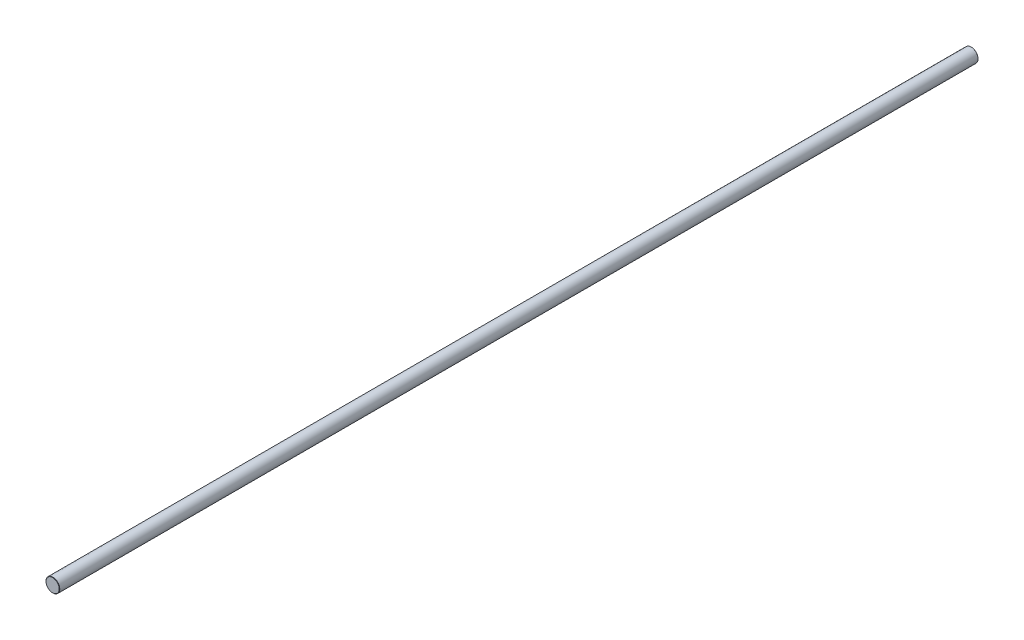
SolidWorks part; units mm, degrees
material "Plain Carbon Steel"
ref_plane "Front Plane" through (0, 0, 0) normal (0, 0, 1) x (1, 0, 0)
ref_plane "Top Plane" through (0, 0, 0) normal (0, 1, 0) x (1, 0, 0)
ref_plane "Right Plane" through (0, 0, 0) normal (1, 0, 0) x (0, 0, -1)
sketch "Sketch1" plane through (0, 0, 0) normal (0, 0, 1) x (1, 0, 0)
  circle A0 centre (0, 0) radius 3 construction
  dimension "Diameter" = 6
sketch "Sketch2" plane through (0, 0, 0) normal (1, 0, 0) x (0, 0, -1)
  line L0 (200, 0) -> (-200, 0) construction
  point P0 (-160, 0)
  point P3 (0, 0)
  point P4 (160, 0)
  point P6 (-140, 0)
  point P7 (140, 0)
  dimension "Length" = 400
  dimension "D1" = 40
  dimension "D2" = 40
  dimension "D3" = 60
  dimension "D4" = 60
sketch "Sketch3" plane through (0, 0, 0) normal (0, 0, 1) x (1, 0, 0)
  circle A0 centre (0, 0) radius 3 construction
  circle A1 centre (0, 0) radius 3
extrude "Boss-Extrude1" add sketch "Sketch3" along normal up to vertex (200 mm away) and the other way up to vertex (200 mm away) up to point (0, 0, 200) other way up to point (0, 0, -200)
chamfer "Chamfer1" distance 0.12 angle 45 2 edges at (3, 0, 200) (3, 0, -200)
equation "\"D1@Chamfer1\"=\"Diameter@Sketch1\"*.02"
equation "\"D1@Sketch2\"=\"D2@Sketch2\""
equation "\"D2@Sketch2\"=\"Length@Sketch2\"*.1"
equation "\"D3@Sketch2\"=\"Length@Sketch2\"*.15"
equation "\"D4@Sketch2\"=\"D3@Sketch2\""
